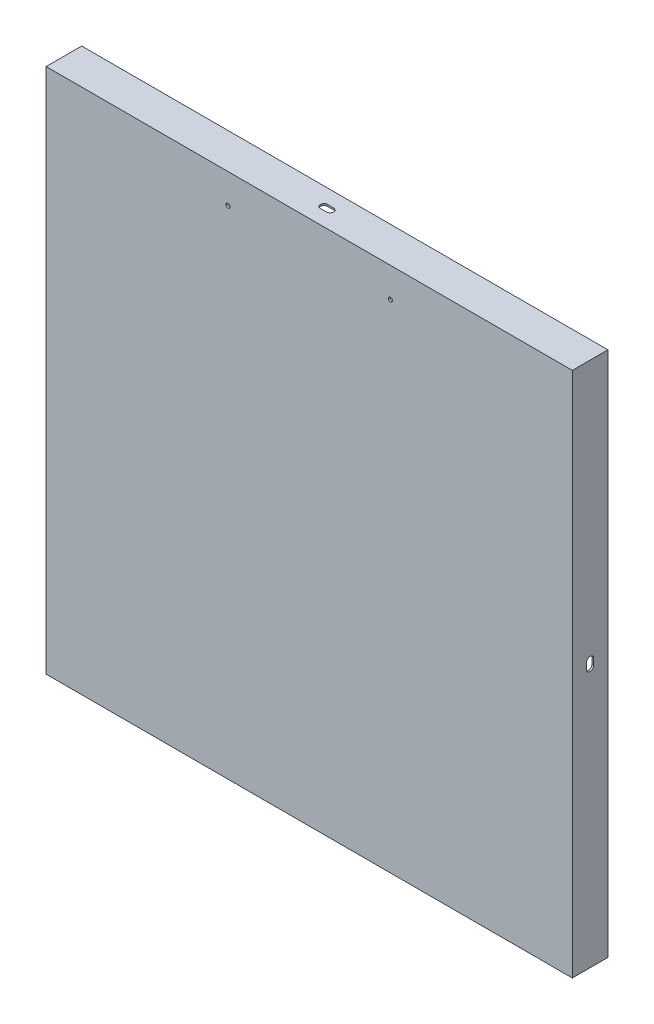
SolidWorks part; units mm, degrees
ref_plane "Piano frontale" through (0, 0, 0) normal (0, 0, 1) x (1, 0, 0)
ref_plane "Piano superiore" through (0, 0, 0) normal (0, 1, 0) x (1, 0, 0)
ref_plane "Piano destro" through (0, 0, 0) normal (1, 0, 0) x (0, 0, -1)
sketch "Schizzo1" plane through (0, 0, 0) normal (0, 0, 1) x (1, 0, 0)
  line L0 (0, 0) -> (0, 444)
  line L1 (0, 444) -> (444, 444)
  line L2 (444, 444) -> (444, 0)
  line L3 (444, 0) -> (0, 0)
  line L4 (0, 222) -> (444, 222) construction
  line L5 (222, 42) -> (222, 123.488) construction
  dimension "D1" = 444
  dimension "D2" = 444
extrude "Estrusione-Estrusione1" add sketch "Schizzo1" against normal blind 30
sketch "Schizzo2" plane through (0, 0, -30) normal (0, 0, -1) x (-1, 0, 0)
  line L1 (-444, 444) -> (0, 444) construction
  line L2 (-222, 444) -> (-222, 0) construction
  line L3 (0, 0) -> (-444, 0) construction
  circle A0 centre (-290.5, 419) radius 1.7
  circle A2 centre (-153.5, 419) radius 1.7
  dimension "D1" = 137
  dimension "D2" = 25
  dimension "D3" = 3.4
extrude "Taglio-Estrusione1" cut sketch "Schizzo2" against normal through all
sketch "Schizzo3" plane through (0, 0, -30) normal (0, 0, -1) x (-1, 0, 0)
  line L0 (-1.5, 1.5) -> (-442.5, 1.5)
  line L1 (-442.5, 1.5) -> (-442.5, 442.5)
  line L2 (-442.5, 442.5) -> (-1.5, 442.5)
  line L3 (-1.5, 442.5) -> (-1.5, 1.5)
  line L4 (58.1657, 222) -> (-551.6329, 222) construction
  line L5 (-222, -121.989) -> (-222, 558.9993) construction
  line L6 (-444, 444) -> (0, 444) construction
  line L7 (0, 0) -> (-444, 0) construction
  line L8 (-444, 0) -> (-444, 444) construction
  line L9 (0, 444) -> (0, 0) construction
  dimension "D1" = 1.5
extrude "Taglio-Estrusione2" cut sketch "Schizzo3" against normal blind 28.5
sketch "Schizzo4" plane through (0, 444, 0) normal (0, 1, 0) x (1, 0, 0)
  line L0 (224.5, 15) -> (219.5, 15) construction
  line L1 (224.5, 12) -> (219.5, 12)
  line L2 (224.5, 18) -> (219.5, 18)
  line L3 (444, 15) -> (0, 15) construction
  line L4 (444, 30) -> (444, 0) construction
  line L5 (0, 30) -> (0, 0) construction
  line L6 (222, 39.4964) -> (222, -17.5035) construction
  arc A0 (224.5, 12) -> (224.5, 18) centre (224.5, 15) ccw
  arc A1 (219.5, 18) -> (219.5, 12) centre (219.5, 15) ccw
  point P2 (222, 15)
  dimension "D2" = 3
  dimension "D1" = 5
extrude "Taglio-Estrusione3" cut sketch "Schizzo4" against normal through all
sketch "Schizzo5" plane through (0, 0, 0) normal (-1, 0, 0) x (0, 0, 1)
  line L0 (-15, 224.5) -> (-15, 219.5) construction
  line L1 (-12, 224.5) -> (-12, 219.5)
  line L2 (-18, 224.5) -> (-18, 219.5)
  line L3 (0, 222) -> (-32.1766, 222) construction
  line L4 (0, 444) -> (0, 0) construction
  line L5 (-15, 444) -> (-15, 0) construction
  line L6 (-30, 444) -> (0, 444) construction
  line L7 (-30, 0) -> (0, 0) construction
  arc A0 (-12, 224.5) -> (-18, 224.5) centre (-15, 224.5) ccw
  arc A1 (-18, 219.5) -> (-12, 219.5) centre (-15, 219.5) ccw
  point P2 (-15, 222)
  dimension "D1" = 3
  dimension "D2" = 5
extrude "Taglio-Estrusione4" cut sketch "Schizzo5" against normal through all
